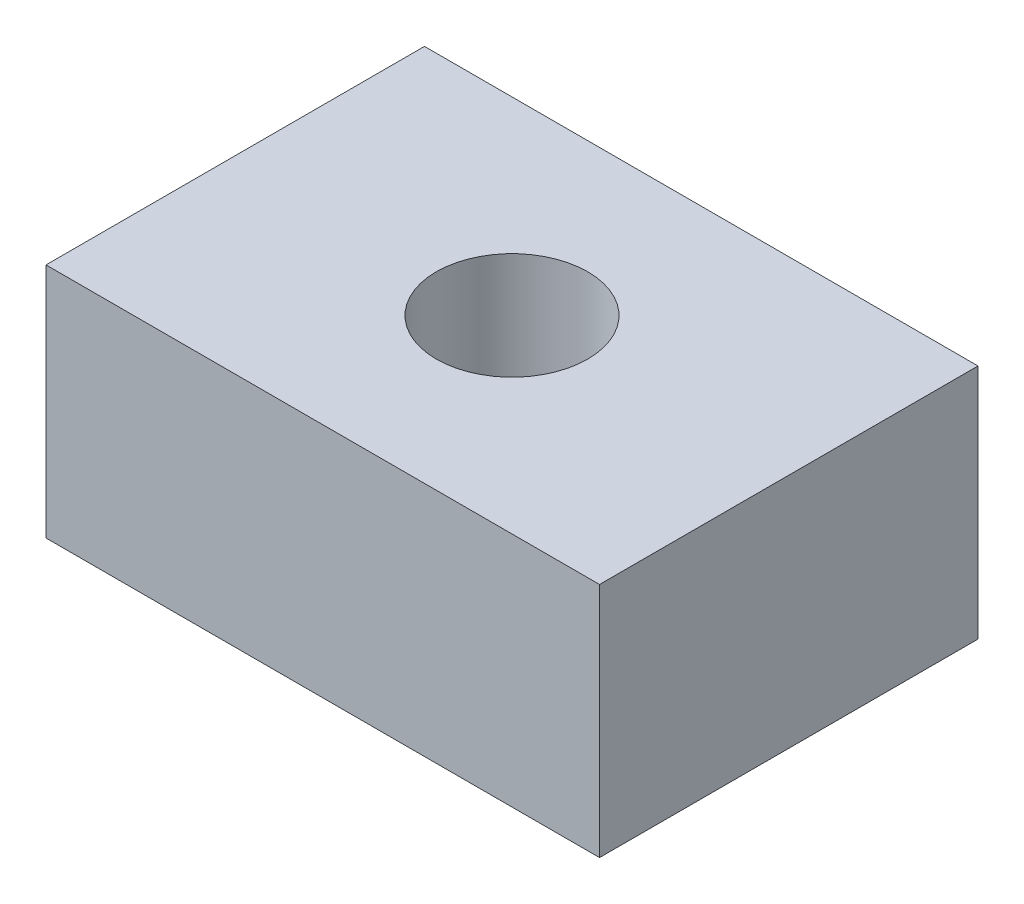
SolidWorks part; units mm, degrees
ref_plane "Front" through (0, 0, 0) normal (0, 0, 1) x (1, 0, 0)
ref_plane "Top" through (0, 0, 0) normal (0, 1, 0) x (1, 0, 0)
ref_plane "Right" through (0, 0, 0) normal (1, 0, 0) x (0, 0, -1)
sketch "Sketch1" plane through (0, 0, 0) normal (0, 1, 0) x (1, 0, 0)
  line L1 (-5.85, 4) -> (5.85, 4)
  line L2 (-5.85, 4) -> (-5.85, -4)
  line L3 (-5.85, -4) -> (5.85, -4)
  line L4 (5.85, 4) -> (5.85, -4)
  line L5 (-5.85, 4) -> (5.85, -4) construction
  line L6 (-5.85, -4) -> (5.85, 4) construction
  point P0 (0, 0)
  dimension "D1" = 8
  dimension "D2" = 11.7
extrude "Boss-Extrude1" add sketch "Sketch1" along normal blind 5
sketch "Sketch2" plane through (0, 5, 0) normal (0, 1, 0) x (1, 0, 0)
  circle A0 centre (0, 0) radius 1.6
  dimension "D1" = 3.2
extrude "Cut-Extrude1" cut sketch "Sketch2" against normal through all
